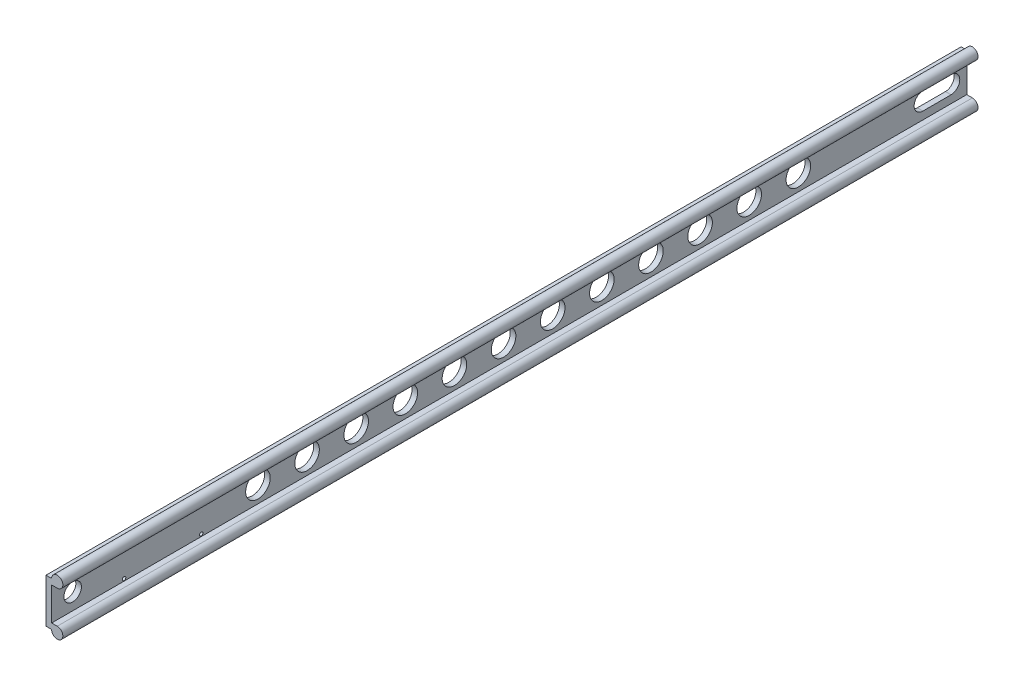
SolidWorks part; units mm, degrees
material "1060 Alloy"
ref_plane "Front Plane" through (0, 0, 0) normal (0, 0, 1) x (1, 0, 0)
ref_plane "Top Plane" through (0, 0, 0) normal (0, 1, 0) x (1, 0, 0)
ref_plane "Right Plane" through (0, 0, 0) normal (1, 0, 0) x (0, 0, -1)
sketch "Sketch1" plane through (0, 0, 0) normal (0, 0, 1) x (1, 0, 0)
  line L0 (-13.1544, 15.9067) -> (-8.0744, 15.9067)
  line L2 (-13.1544, 15.9067) -> (-13.1544, -24.0983)
  line L4 (-8.0744, 10.8267) -> (-8.0744, -19.0183)
  line L5 (-13.1544, -24.0983) -> (-8.0744, -24.0983)
  line L6 (-2.9944, -19.0183) -> (-8.0744, -19.0183)
  line L7 (-2.9944, 10.8267) -> (-8.0744, 10.8267)
  arc A2 (-2.9944, 10.8267) -> (-8.0744, 15.9067) centre (-2.9944, 15.9067) ccw
  arc A3 (-8.0744, -24.0983) -> (-2.9944, -19.0183) centre (-2.9944, -24.0983) ccw
  dimension "D3" = 10.16
  dimension "D4" = 10.16
  dimension "D1" = 5.08
  dimension "D2" = 40.005
extrude "Boss-Extrude1" add sketch "Sketch1" along normal blind 828.04
sketch "Sketch2" plane through (-13.1544, 0, 0) normal (-1, 0, 0) x (0, 0, 1)
  line L1 (0, -55) -> (0, 55) construction
  line L2 (828.04, 15.9067) -> (0, 15.9067) construction
  circle A0 centre (152.4, -4.0958) radius 11.1125
  dimension "D1" = 20.0025
  dimension "D3" = 22.225
  dimension "D2" = 152.4
extrude "Cut-Extrude1" cut sketch "Sketch2" against normal blind 25.4
pattern_linear "LPattern1" count 12 spacing 44.45 along (0, 0, 1) of "Cut-Extrude1"
sketch "Sketch3" plane through (-13.1544, 0, 0) normal (-1, 0, 0) x (0, 0, 1)
  line L0 (828.04, 15.9067) -> (0, 15.9067) construction
  line L1 (0, -55) -> (0, 55) construction
  line L3 (828.04, 15.9067) -> (828.04, -24.0983) construction
  line L4 (14.2875, 3.8417) -> (39.6875, 3.8417)
  line L5 (14.2875, -12.0333) -> (39.6875, -12.0333)
  circle A1 centre (808.99, -4.0958) radius 7.9375
  arc A2 (14.2875, 3.8417) -> (14.2875, -12.0333) centre (14.2875, -4.0958) ccw
  arc A3 (39.6875, 3.8417) -> (39.6875, -12.0333) centre (39.6875, -4.0958) cw
  dimension "D1" = 14.2875
  dimension "D3" = 15.875
  dimension "D6" = 25.4
  dimension "D7" = 7.9375
  dimension "D2" = 20.0025
  dimension "D4" = 20.0025
  dimension "D5" = 19.05
extrude "Cut-Extrude2" cut sketch "Sketch3" against normal blind 25.4
sketch "Sketch5" plane through (-13.1544, 0, 0) normal (-1, 0, 0) x (0, 0, 1)
  line L0 (828.04, 15.9067) -> (0, 15.9067) construction
  line L1 (828.04, -24.0983) -> (0, -24.0983) construction
  line L2 (828.04, 15.9067) -> (828.04, -24.0983) construction
  circle A0 centre (692.658, 8.7947) radius 1.5875
  circle A1 centre (762.508, 8.7947) radius 1.5875
  circle A2 centre (762.508, -16.9863) radius 1.5875
  circle A3 centre (692.658, -16.9863) radius 1.5875
  dimension "D1" = 3.175
  dimension "D2" = 7.112
  dimension "D3" = 7.112
  dimension "D4" = 65.532
  dimension "D5" = 135.382
extrude "Cut-Extrude3" cut sketch "Sketch5" against normal blind 12.7
